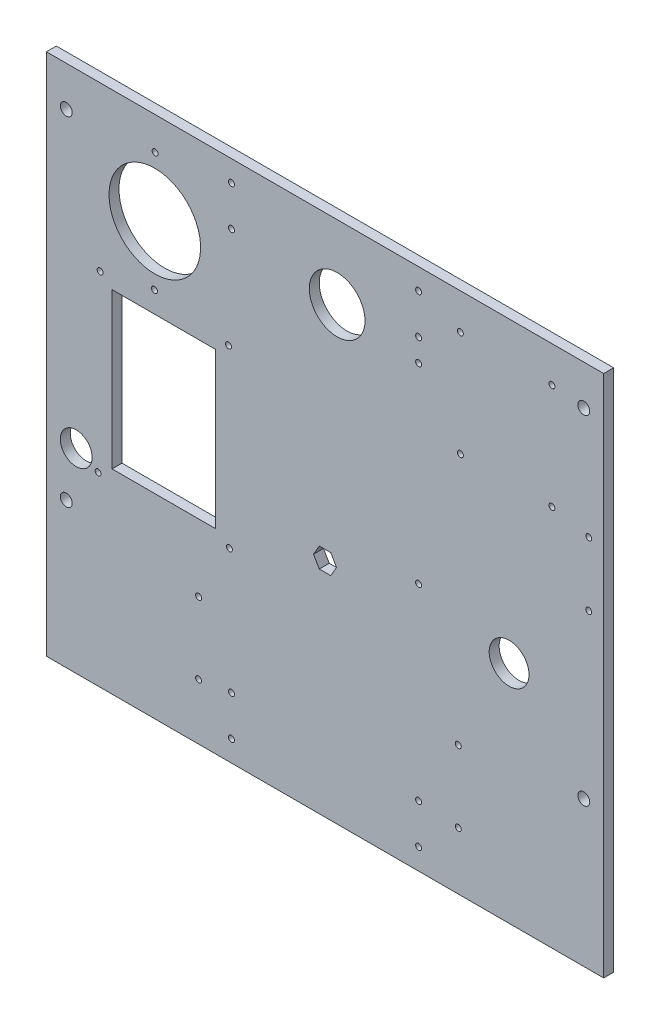
SolidWorks part; units mm, degrees
ref_plane "Plan de face" through (0, 0, 0) normal (0, 0, 1) x (1, 0, 0)
ref_plane "Plan de dessus" through (0, 0, 0) normal (0, 1, 0) x (1, 0, 0)
ref_plane "Plan de droite" through (0, 0, 0) normal (1, 0, 0) x (0, 0, -1)
sketch "Esquisse1" plane through (0, 0, 0) normal (0, 0, 1) x (1, 0, 0)
  line L1 (0, 0) -> (280, 0)
  line L2 (0, 0) -> (0, 210)
  line L3 (0, 210) -> (280, 210)
  line L4 (280, 0) -> (280, 210)
  dimension "D1" = 210
  dimension "D2" = 280
extrude "Boss.-Extru.1" add sketch "Esquisse1" along normal blind 5
sketch "Esquisse2" plane through (0, 0, 0) normal (0, 0, 1) x (1, 0, 0)
  line L0 (280, 210) -> (0, 210) construction
  line L1 (85, 123) -> (33, 123)
  line L2 (0, 0) -> (280, 0) construction
  line L3 (0, 0) -> (0, 210) construction
  line L4 (0, 210) -> (280, 210) construction
  line L5 (280, 0) -> (280, 210) construction
  line L6 (85, 123) -> (85, 45)
  line L7 (137.1132, 63.5) -> (134.2265, 58.5)
  line L8 (134.2265, 58.5) -> (137.1132, 53.5)
  line L9 (137.1132, 53.5) -> (142.8868, 53.5)
  line L10 (142.8868, 53.5) -> (145.7735, 58.5)
  line L11 (145.7735, 58.5) -> (142.8868, 63.5)
  line L12 (142.8868, 63.5) -> (137.1132, 63.5)
  line L13 (85, 45) -> (33, 45)
  line L14 (33, 123) -> (33, 45)
  circle A0 centre (270, 190) radius 3
  circle A1 centre (10, 190) radius 3
  circle A2 centre (10, 20) radius 3
  circle A3 centre (270, 20) radius 3
  circle A4 centre (140, 58.5) radius 5 construction
  circle A5 centre (187, 168) radius 1.5
  circle A6 centre (187, 72) radius 1.5
  circle A7 centre (91.5, 128) radius 1.5
  circle A8 centre (27, 128) radius 1.5
  circle A9 centre (92, 40) radius 1.5
  circle A10 centre (26, 40) radius 1.5
  circle A11 centre (15, 45) radius 8
  circle A12 centre (146.0937, 173) radius 14
  circle A13 centre (232.4771, 60.1974) radius 10
  circle A14 centre (272.5, 103) radius 1.5
  circle A15 centre (272.5, 135) radius 1.5
  dimension "D1" = 6
  dimension "D2" = 6
  dimension "D3" = 6
  dimension "D4" = 6
  dimension "D5" = 20
  dimension "D6" = 10
  dimension "D7" = 20
  dimension "D8" = 10
  dimension "D9" = 10
  dimension "D10" = 20
  dimension "D11" = 10
  dimension "D12" = 20
  dimension "D13" = 10
  dimension "D14" = 3
  dimension "D15" = 3
  dimension "D16" = 96
  dimension "D17" = 93
  dimension "D19" = 5
  dimension "D26" = 7
  dimension "D27" = 5
  dimension "D29" = 6.5
  dimension "D30" = 5
  dimension "D32" = 3
  dimension "D33" = 3
  dimension "D34" = 3
  dimension "D35" = 3
  dimension "D37" = 42
  dimension "D38" = 16
  dimension "D39" = 28
  dimension "D40" = 20
  dimension "D18" = 93
  dimension "D41" = 3
  dimension "D42" = 3
  dimension "D43" = 7.5
  dimension "D44" = 7.5
  dimension "D45" = 32
  dimension "D46" = 75
  dimension "D20" = 52
  dimension "D21" = 78
  dimension "D22" = 45
  dimension "D23" = 85
  dimension "D24" = 5
  dimension "D25" = 7
  dimension "D28" = 5
  dimension "D31" = 6
  dimension "D36" = 18
  dimension "D47" = 151.5
  dimension "D48" = 140
extrude "Enlèv. mat.-Extru.1" cut sketch "Esquisse2" along normal through all
sketch "Esquisse5" plane through (0, 0, 0) normal (0, 0, -1) x (-1, 0, 0)
  circle A0 centre (-93, 179.4) radius 1.5
  circle A1 centre (-93, 199.4) radius 1.5
  circle A2 centre (-187, 199.4) radius 1.5
  circle A3 centre (-187, 179.4) radius 1.5
  dimension "D1" = 3
  dimension "D2" = 3
  dimension "D3" = 3
  dimension "D4" = 3
extrude "Enlèv. mat.-Extru.3" cut sketch "Esquisse5" against normal through all
sketch "Esquisse6" plane through (0, 0, 0) normal (0, 0, -1) x (-1, 0, 0)
  line L1 (-280, 0) -> (0, 0)
  line L2 (-280, 0) -> (-280, -53)
  line L3 (-280, -53) -> (0, -53)
  line L4 (0, 0) -> (0, -53)
  point P5 (-280, -26.5)
  dimension "D1" = 53
  dimension "D2" = 280
extrude "Boss.-Extru.4" add sketch "Esquisse6" against normal blind 5
sketch "Esquisse7" plane through (0, 0, 0) normal (0, 0, -1) x (-1, 0, 0)
  circle A0 centre (-76.4853, 11.1492) radius 1.5
  circle A3 centre (-76.4733, -24.8348) radius 1.5
  dimension "D3" = 3
  dimension "D4" = 3
extrude "Enlèv. mat.-Extru.4" cut sketch "Esquisse7" against normal through all
sketch "Esquisse8" plane through (0, 0, 0) normal (0, 0, -1) x (-1, 0, 0)
  circle A0 centre (-206.9449, -24.14) radius 1.5
  circle A1 centre (-206.9449, 11.844) radius 1.5
  dimension "D2" = 3
  dimension "D3" = 3
extrude "Enlèv. mat.-Extru.5" cut sketch "Esquisse8" against normal through all
sketch "Esquisse9" plane through (0, 0, 0) normal (0, 0, -1) x (-1, 0, 0)
  circle A0 centre (-93, -22.4) radius 1.5
  circle A1 centre (-93, -42.4) radius 1.5
  circle A2 centre (-93, -42.4) radius 1.5 construction
  circle A3 centre (-187, -42.4) radius 1.5
  circle A4 centre (-187, -22.4) radius 1.5
  dimension "D1" = 3
  dimension "D2" = 3
  dimension "D3" = 0
  dimension "D4" = 3
  dimension "D5" = 3
extrude "Enlèv. mat.-Extru.6" cut sketch "Esquisse9" against normal through all
sketch "Esquisse14" plane through (0, 0, 0) normal (0, 0, -1) x (-1, 0, 0)
  circle A0 centre (-54.4827, 163.5701) radius 23
  circle A1 centre (-54.6491, 193.5697) radius 1.5
  circle A2 centre (-54.3162, 133.5706) radius 1.5
  dimension "D1" = 3
  dimension "D2" = 46
  dimension "D3" = 3
extrude "Enlèv. mat.-Extru.11" cut sketch "Esquisse14" against normal through all
sketch "Esquisse15" plane through (0, 0, 5) normal (0, 0, 1) x (1, 0, 0)
  circle A0 centre (254, 192) radius 1.5
  circle A1 centre (208, 192) radius 1.5
  circle A2 centre (208, 139) radius 1.5
  circle A3 centre (254, 139) radius 1.5
  dimension "D1" = 3
  dimension "D2" = 3
  dimension "D3" = 3
  dimension "D4" = 3
extrude "Enlèv. mat.-Extru.12" cut sketch "Esquisse15" against normal through all
